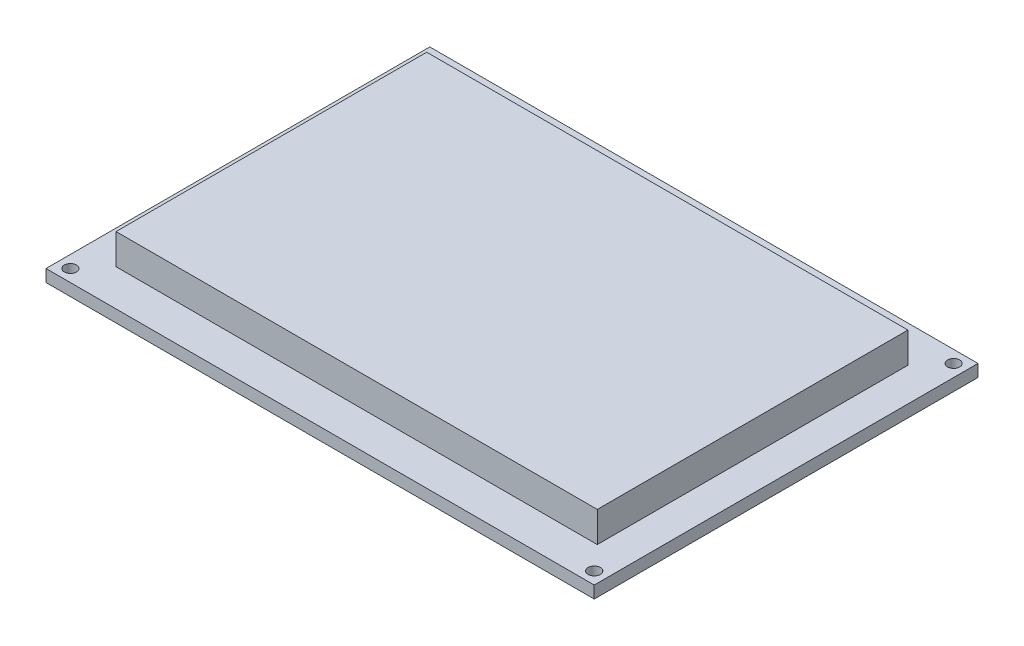
SolidWorks part; units mm, degrees
ref_plane "前视基准面" through (0, 0, 0) normal (0, 0, 1) x (1, 0, 0)
ref_plane "上视基准面" through (0, 0, 0) normal (0, 1, 0) x (1, 0, 0)
ref_plane "右视基准面" through (0, 0, 0) normal (1, 0, 0) x (0, 0, -1)
sketch "草图1" plane through (0, 0, 0) normal (0, 1, 0) x (1, 0, 0)
  line L1 (-30.121, 18.5181) -> (59.879, 18.5181)
  line L2 (-30.121, 18.5181) -> (-30.121, -44.4819)
  line L3 (-30.121, -44.4819) -> (59.879, -44.4819)
  line L4 (59.879, 18.5181) -> (59.879, -44.4819)
  line L5 (-30.121, 18.5181) -> (59.879, -44.4819) construction
  line L6 (-30.121, -44.4819) -> (59.879, 18.5181) construction
  point P4 (14.879, -12.9819)
  dimension "D1" = 63
  dimension "D2" = 90
extrude "凸台-拉伸1" add sketch "草图1" along normal blind 2
sketch "草图2" plane through (0, 2, 0) normal (0, 1, 0) x (1, 0, 0)
  line L0 (-30.121, -12.9819) -> (59.879, -12.9819) construction
  line L1 (-30.121, 18.5181) -> (-30.121, -44.4819) construction
  line L2 (59.879, -44.4819) -> (59.879, 18.5181) construction
  line L4 (-24.621, 12.5181) -> (54.379, 12.5181)
  line L5 (-24.621, 12.5181) -> (-24.621, -38.4819)
  line L6 (-24.621, -38.4819) -> (54.379, -38.4819)
  line L7 (54.379, 12.5181) -> (54.379, -38.4819)
  line L8 (14.879, -38.4819) -> (14.879, 12.5181) construction
  line L9 (-24.621, -12.9819) -> (54.379, -12.9819) construction
  point P6 (14.879, -12.9819)
  dimension "D1" = 79
  dimension "D2" = 51
extrude "凸台-拉伸2" add sketch "草图2" along normal blind 5
sketch "草图3" plane through (0, 2, 0) normal (0, 1, 0) x (1, 0, 0)
  line L0 (-28.121, 18.5181) -> (-28.121, -44.4819) construction
  line L1 (59.879, 18.5181) -> (-30.121, 18.5181) construction
  line L2 (-30.121, -44.4819) -> (59.879, -44.4819) construction
  line L3 (57.879, 18.5181) -> (57.879, -44.4819) construction
  line L4 (-30.121, 18.5181) -> (-30.121, -44.4819) construction
  line L5 (59.879, -44.4819) -> (59.879, 18.5181) construction
  circle A0 centre (-28.121, 16.5181) radius 1
  circle A1 centre (-28.121, -42.4819) radius 1
  circle A2 centre (57.879, -42.4819) radius 1
  circle A3 centre (57.879, 16.5181) radius 1
  dimension "D1" = 2
  dimension "D2" = 2
  dimension "D3" = 2
  dimension "D4" = 2
  dimension "D5" = 2
  dimension "D6" = 2
  dimension "D7" = 2
extrude "切除-拉伸1" cut sketch "草图3" against normal through all
